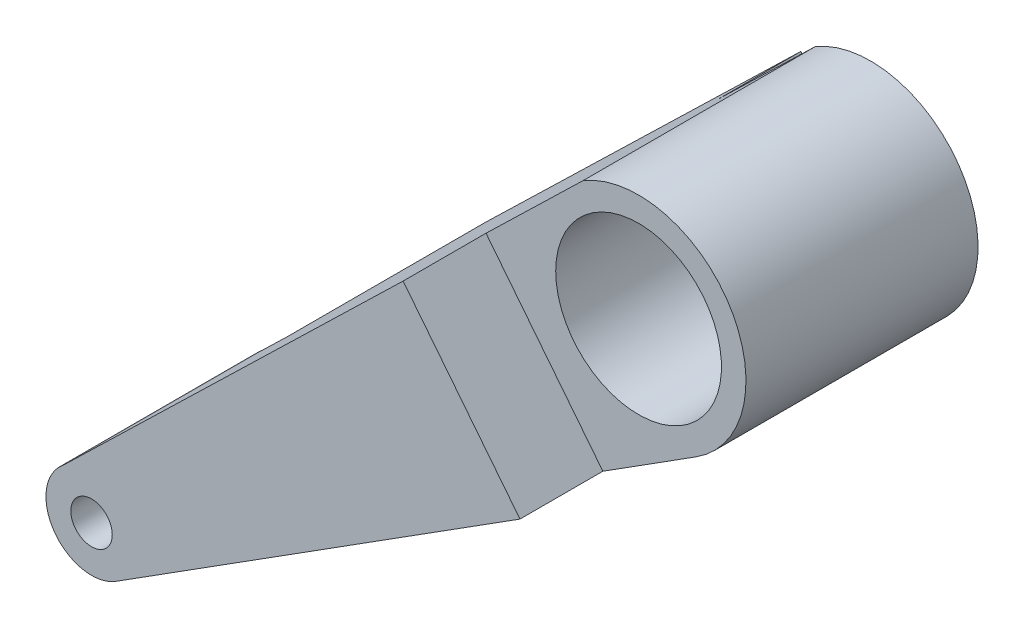
SolidWorks part; units mm, degrees
ref_plane "前视基准面" through (0, 0, 0) normal (0, 0, 1) x (1, 0, 0)
ref_plane "上视基准面" through (0, 0, 0) normal (0, 1, 0) x (1, 0, 0)
ref_plane "右视基准面" through (0, 0, 0) normal (1, 0, 0) x (0, 0, -1)
sketch "草图3" plane through (0, 0, 0) normal (0, 0, 1) x (1, 0, 0)
  line L0 (-66.1813, -39.4809) -> (-79.3564, -52.2493)
  line L1 (-62.7665, -44.9867) -> (-77.7642, -54.4866)
  circle A0 centre (-64.5, -42.25) radius 2.5 construction
  circle A1 centre (-64.5, -42.25) radius 2.5
  circle A2 centre (-64.5, -42.25) radius 3.2396
  circle A3 centre (-78.5, -53.325) radius 0.625
  circle A4 centre (-78.5, -53.325) radius 1.375
  line M8 (-72.1234, -43.9699) -> (-68.8695, -46.5639)
  arc M9 (-68.8695, -46.5639) -> (-67.6228, -47) centre (-67.6228, -45) ccw
  line M10 (-67.6228, -47) -> (-61.875, -47)
  circle M11 centre (-64.5, -42.25) radius 2.5
  dimension "D1" = 1.25
  dimension "D2" = 2.75
  dimension "D5" = 6.4791
  dimension "D3" = 11.075
  dimension "D4" = 14
extrude "凸台-拉伸1" add sketch "草图3" along normal up to surface (12 mm away) contours L0 A2 M11 | A2 L0 L1 M8 M9 M10 | A4 A3 | A4 L1 L0 M10 M9 M8
ref_plane "基准面4" through (0, 0, 6) normal (0, 0, 1) x (1, 0, 0)
sketch "草图4" plane through (0, 0, 6) normal (0, 0, 1) x (1, 0, 0)
  circle A0 centre (-78.5, -53.325) radius 1.375
  circle A1 centre (-78.5, -53.325) radius 0.625 construction
  circle A2 centre (-78.5, -53.325) radius 0.625
extrude "切除-拉伸1" cut sketch "草图4" against normal up to surface (6 mm away) up to face at (-62, -42.25, 0)
sketch "草图5" plane through (0, 0, 0) normal (0, 0, -1) x (-1, 0, 0)
  line L1 (78.3285, -51.1092) -> (79.6915, -51.1092)
  line L2 (62.7665, -44.9867) -> (77.7642, -54.4866)
  line L3 (79.3564, -52.2493) -> (66.1813, -39.4809)
  line L4 (62.7665, -44.9867) -> (76.7736, -53.8591)
  line L5 (79.3564, -52.2493) -> (66.1813, -39.4809)
  line L6 (78.3285, -51.1092) -> (78.3285, -52.568)
  line L7 (78.3285, -52.568) -> (79.6915, -52.568)
  line L8 (79.6915, -51.1092) -> (79.6915, -52.568)
  line L9 (76.5597, -53.006) -> (77.8325, -53.006)
  line L10 (76.5597, -53.006) -> (76.5597, -54.6264)
  line L11 (76.5597, -54.6264) -> (77.8325, -54.6264)
  line L12 (77.8325, -53.006) -> (77.8325, -54.6264)
  arc A0 (76.7736, -53.8591) -> (77.1524, -53.5982) centre (76.9074, -53.6479) ccw
  circle A1 centre (78.4319, -51.7014) radius 0.25
  arc A2 (79.3564, -52.2493) -> (77.7642, -54.4866) centre (78.5, -53.325) ccw
  arc A3 (66.1813, -39.4809) -> (62.7665, -44.9867) centre (64.5, -42.25) ccw
  arc A4 (79.3564, -52.2493) -> (77.1524, -53.5982) centre (78.5, -53.325) ccw
  arc A5 (66.1813, -39.4809) -> (62.7665, -44.9867) centre (64.5, -42.25) ccw
  line M12 (62.7665, -44.9867) -> (77.7642, -54.4866)
  arc M13 (77.7642, -54.4866) -> (79.3564, -52.2493) centre (78.5, -53.325) cw
  line M14 (79.3564, -52.2493) -> (66.1813, -39.4809)
  dimension "D2" = 0.25
  dimension "D3" = 0.5
  dimension "D1" = 0
extrude "切除-拉伸2" cut sketch "草图5" against normal up to surface (6 mm away) contours A1 M13 M14 | L8 L1 L6 L5 L7 M14 M13 | L12 L9 L4 L10 L11 M13 M12 | A0 M12 M13 up to face at (-77.875, -53.325, 6)
sketch "草图6" plane through (0, 0, 0) normal (0, 0, -1) x (-1, 0, 0)
  line L0 (64.5, -42.25) -> (78.5, -53.325)
sketch "草图7" plane through (0, 0, 12) normal (0, 0, 1) x (1, 0, 0)
  line L0 (-64.5, -42.25) -> (-78.5, -53.325)
ref_plane "基准面5" through (-4.2693, 5.3968, 0) normal (0.6204, -0.7843, 0) x (-0.7843, -0.6204, 0)
sketch "草图9" plane through (-4.2693, 5.3968, 0) normal (0.6204, -0.7843, 0) x (-0.7843, -0.6204, 0)
  line L0 (71.9453, -9.5) -> (74.2988, -9.5)
  line L1 (75.9651, -9.5) -> (71.9453, -9.5) construction
  line L2 (71.9453, -6) -> (75.7051, -6)
  line L3 (80.4453, -12) -> (73.4107, -12)
  line L4 (80.4453, -12) -> (80.4453, -9.5)
  line L5 (80.4453, -9.5) -> (73.4107, -9.5)
  line L6 (73.4107, -12) -> (73.4107, -9.5)
  line L7 (71.9453, -2.5) -> (71.9453, -9.5) construction
  line L8 (73.4107, 0) -> (73.4107, -2.5)
  line L9 (80.4453, -2.5) -> (73.4107, -2.5)
  line L10 (80.4453, 0) -> (80.4453, -2.5)
  line L11 (80.4453, 0) -> (73.4107, 0)
  line L12 (71.9453, -2.5) -> (74.2988, -2.5)
  line L13 (69.9846, 0) -> (74.0044, 0) construction
  dimension "D1" = 8.5
extrude "切除-拉伸3" cut sketch "草图9" against normal through all both and the other way through all contours L10 L11 L8 L9 | L6 L3 L4 L5 L0
